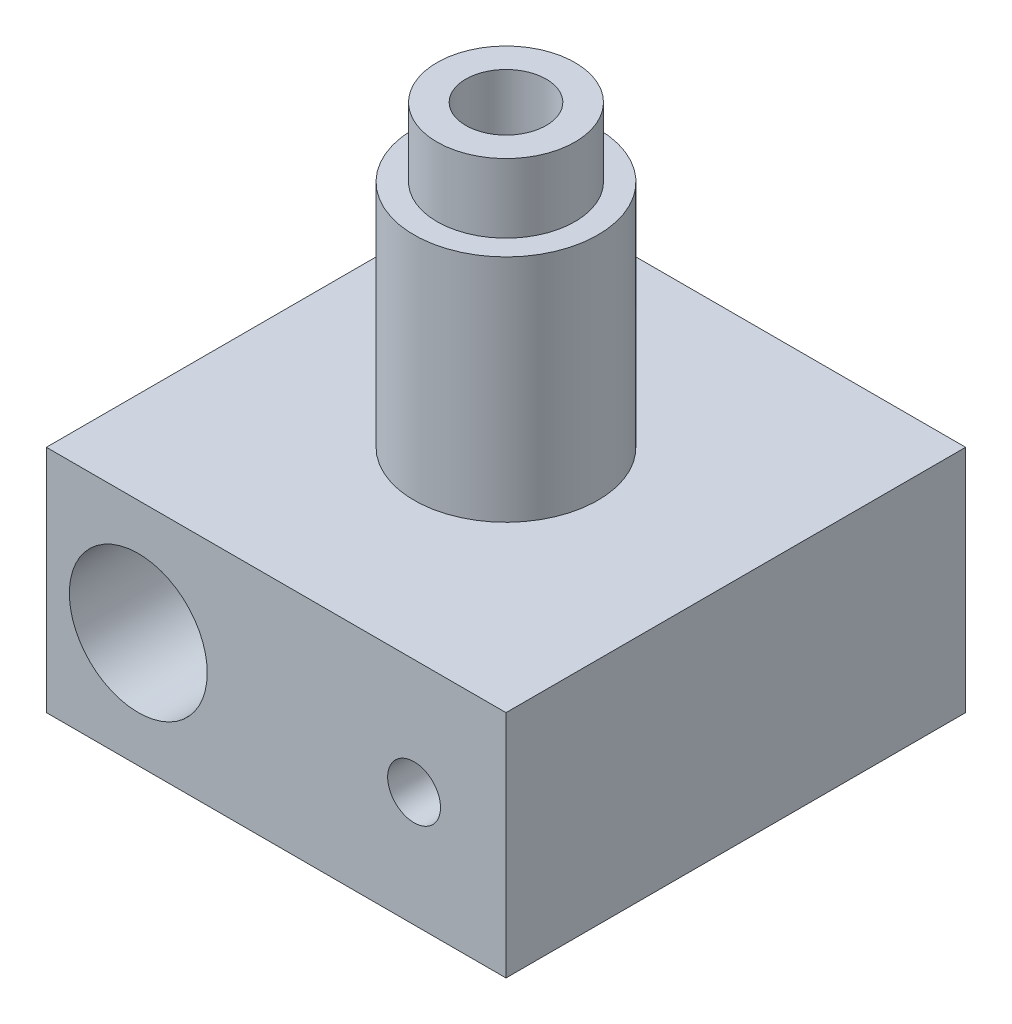
SolidWorks part; units mm, degrees
material "7075-T6 (SN)"
ref_plane "Piano frontale" through (0, 0, 0) normal (0, 0, 1) x (1, 0, 0)
ref_plane "Piano superiore" through (0, 0, 0) normal (0, 1, 0) x (1, 0, 0)
ref_plane "Piano destro" through (0, 0, 0) normal (1, 0, 0) x (0, 0, -1)
sketch "Schizzo1" plane through (0, 0, 0) normal (0, 0, 1) x (1, 0, 0)
  line L0 (-0.15, 0) -> (-0.15, -5)
  line L1 (-0.15, -5) -> (-0.5, -5)
  line L2 (-0.5, -5) -> (-3, -2)
  line L3 (-3, -2) -> (-3, 0)
  line L4 (-3, 0) -> (-0.15, 0)
  line L5 (0, -26.5282) -> (0, 14.9614) construction
  dimension "D1" = 0.3
  dimension "D2" = 5
  dimension "D3" = 6
  dimension "D4" = 1
  dimension "D5" = 2
revolve "Rivoluzione1" add sketch "Schizzo1" angle 360 about L5
sketch "Schizzo2" plane through (0, 0, 0) normal (0, 1, 0) x (1, 0, 0)
  line L0 (0, 0) -> (0, -10.5487) construction
  line L6 (10, -10) -> (-10, -10)
  line L7 (10, -10) -> (10, 10)
  line L8 (10, 10) -> (-10, 10)
  line L9 (-10, -10) -> (-10, 10)
  line L10 (10, -10) -> (-10, 10) construction
  line L11 (10, 10) -> (-10, -10) construction
  circle A1 centre (0, 0) radius 0.15 construction
  circle A2 centre (0, 0) radius 0.15
  dimension "D1" = 20
  dimension "D2" = 20
extrude "Estrusione-Estrusione1" add sketch "Schizzo2" along normal blind 10
sketch "Schizzo3" plane through (0, 10, 0) normal (0, 1, 0) x (1, 0, 0)
  circle A0 centre (0, 0) radius 4
extrude "Estrusione-Sottile1" add sketch "Schizzo3" along normal blind 13 thin thin type one direction reverse wall 2.25
sketch "Schizzo4" plane through (0, 0, 10) normal (0, 0, 1) x (1, 0, 0)
  line L0 (-10, 5) -> (10, 5) construction
  line L1 (-10, 10) -> (-10, 0) construction
  line L2 (10, 10) -> (10, 0) construction
  circle A0 centre (-6, 5) radius 3
  circle A1 centre (6, 5) radius 1.15
  dimension "D1" = 4
  dimension "D2" = 6
  dimension "D3" = 2.3
  dimension "D4" = 4
extrude "Taglio-Estrusione1" cut sketch "Schizzo4" against normal up to next
sketch "Schizzo5" plane through (0, 0, -10) normal (0, 0, -1) x (-1, 0, 0)
  circle A0 centre (-6, 5) radius 3
hole_wizard "Foro filettato M6x1.0-1" positions "Schizzo7" profile "Schizzo6" tap size "M6x1.0" standard "Ansi Metric"
sketch "Schizzo7" plane through (0, 0, -10) normal (0, 0, -1) x (-1, 0, 0)
  point P1 (-6, 5)
sketch "Schizzo6" plane through (6, 5, -10) normal (1, 0, 0) x (0, 1, 0)
  line L0 (0, 0) -> (0, 13.5022)
  line L1 (0, 13.5022) -> (2.5, 12)
  line L2 (2.5, 12) -> (2.5, 0.525)
  line L3 (2.5, 0.525) -> (3.025, 0)
  line L5 (3.025, 0) -> (0, 0)
  line L6 (-2.5, 0.525) -> (-3.025, 0) construction
  line L10 (0, 13.5022) -> (-2.5, 12) construction
  line L11 (0, -6.35) -> (0, 107.95) construction
  dimension "Tap Drill Dia." = 5
  dimension "Tap Drill Depth" = 12
  dimension "Near C'Sink Dia." = 6.05
  dimension "Near C'Sink Angle" = 90
  dimension "Drill Angle" = 118
cosmetic thread "Filettatura del foro1" parameters "D1"=12, "D2"=6
sketch "Schizzo8" plane through (0, 23, 0) normal (0, 1, 0) x (1, 0, 0)
  circle A0 centre (0, 0) radius 3
extrude "Taglio-Estrusione-Sottile1" cut sketch "Schizzo8" against normal blind 3 thin
equation "\"50di\"=45"
